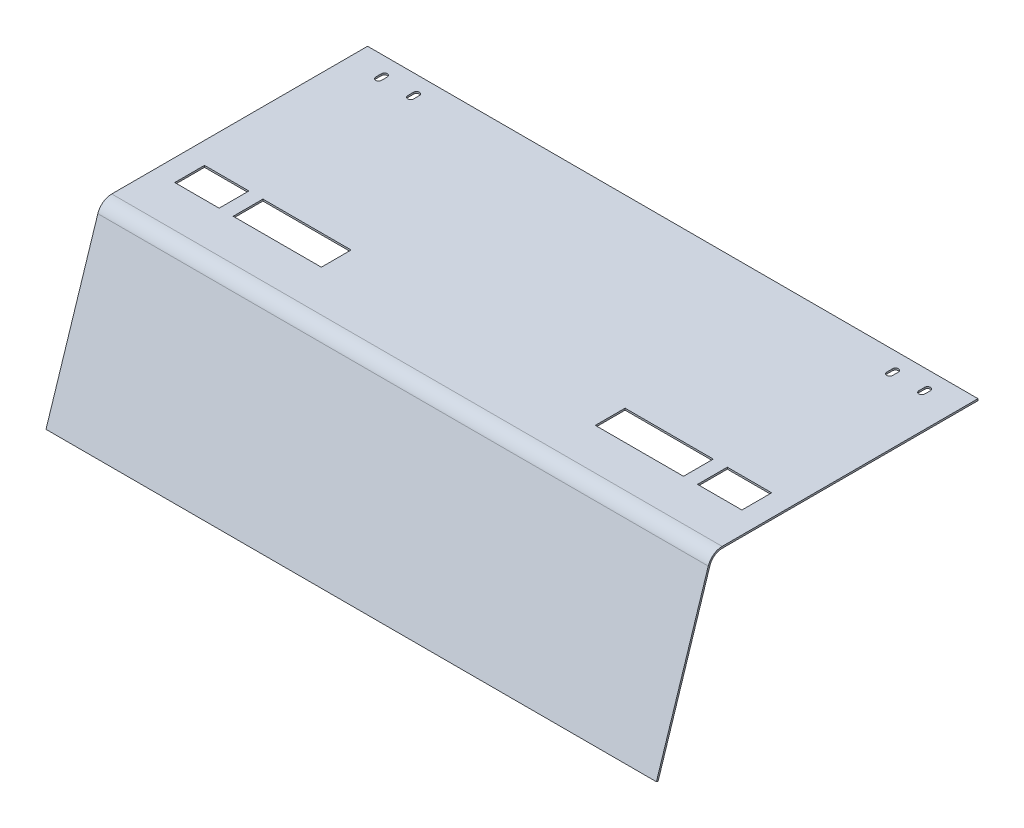
SolidWorks part; units mm, degrees
material "6061 합금"
ref_plane "정면" through (0, 0, 0) normal (0, 0, 1) x (1, 0, 0)
ref_plane "윗면" through (0, 0, 0) normal (0, 1, 0) x (1, 0, 0)
ref_plane "우측면" through (0, 0, 0) normal (1, 0, 0) x (0, 0, -1)
sketch "스케치1" plane through (0, 0, 0) normal (0, 1, 0) x (1, 0, 0)
  line L0 (-209, 87.105) -> (-209, -88.105)
  line L1 (-210, 88.105) -> (210, 88.105) construction
  line L2 (-210, 88.105) -> (-210, -88.105) construction
  line L3 (-210, -88.105) -> (210, -88.105) construction
  line L4 (210, 88.105) -> (210, -88.105) construction
  line L5 (-210, 88.105) -> (210, -88.105) construction
  line L6 (-210, -88.105) -> (210, 88.105) construction
  line L7 (-209, 87.105) -> (209, 87.105)
  line L8 (209, 87.105) -> (209, -88.105)
  line L9 (-209, -88.105) -> (209, -88.105)
  point P0 (0, 0)
  dimension "D1" = 176.21
  dimension "D2" = 420
  dimension "D3" = 1
extrude "보스-돌출1" add sketch "스케치1" along normal blind 1.2
sketch "스케치2" plane through (0, 0, 0) normal (1, 0, 0) x (0, 0, -1)
  line L0 (-97.6231, -5.7331) -> (-133.1196, -115.8954)
  line L7 (-96.4809, -6.1011) -> (-131.9775, -116.2635)
  line L8 (-133.1196, -115.8954) -> (-131.9775, -116.2635)
  line L10 (-88.105, 0) -> (87.105, 0)
  line L11 (87.105, 0) -> (87.105, 1.2)
  line L12 (87.105, 1.2) -> (-88.105, 1.2)
  line L13 (-88.105, 1.2) -> (-88.105, 0)
  line L17 (-88.105, 1.2) -> (-88.105, 0)
  arc A0 (-88.105, 1.2) -> (-97.6231, -5.7331) centre (-88.105, -8.8) ccw
  arc A1 (-88.105, 0) -> (-96.4809, -6.1011) centre (-88.105, -8.8) ccw
  dimension "D1" = 0
  dimension "D4" = 115.74
  dimension "D5" = 1.2
extrude "보스-돌출2" add sketch "스케치2" along normal up to vertex (209 mm away) and the other way up to vertex (209 mm away) up to point (209, 1.2, 88.105) other way up to point (-209, 1.2, 88.105)
sketch "스케치3" plane through (0, 1.2, 0) normal (0, 1, 0) x (1, 0, 0)
  line L0 (0, -87.105) -> (0, 87.105) construction
  line L1 (209, 87.105) -> (-209, 87.105) construction
  line L2 (-209, 87.105) -> (-209, -88.105) construction
  line L3 (-190, 87.105) -> (-160, 87.105)
  line L4 (-190, 87.105) -> (-190, 68.605)
  line L5 (-190, 68.605) -> (-160, 68.605)
  line L6 (-160, 87.105) -> (-160, 68.605)
  line L7 (-190, 73.605) -> (-160, 73.605) construction
  line L8 (-175, 87.105) -> (-175, 68.605) construction
  line L9 (-162, 75.605) -> (-162, 71.605)
  line L10 (-166, 75.605) -> (-166, 71.605)
  line L11 (-184, 75.605) -> (-184, 71.605)
  line L12 (-188, 75.605) -> (-188, 71.605)
  line L13 (175, 87.105) -> (175, 68.605) construction
  line L14 (190, 73.605) -> (160, 73.605) construction
  line L15 (188, 75.605) -> (188, 71.605)
  line L16 (184, 75.605) -> (184, 71.605)
  line L17 (166, 75.605) -> (166, 71.605)
  line L18 (162, 75.605) -> (162, 71.605)
  line L19 (160, 87.105) -> (160, 68.605)
  line L20 (190, 68.605) -> (160, 68.605)
  line L21 (190, 87.105) -> (190, 68.605)
  line L22 (190, 87.105) -> (160, 87.105)
  circle A0 centre (-164, 73.605) radius 2
  circle A1 centre (-164, 71.605) radius 2
  circle A2 centre (-164, 75.605) radius 2
  circle A3 centre (-186, 75.605) radius 2
  circle A4 centre (-186, 71.605) radius 2
  circle A5 centre (-186, 73.605) radius 2
  circle A6 centre (186, 73.605) radius 2
  circle A7 centre (186, 71.605) radius 2
  circle A8 centre (186, 75.605) radius 2
  circle A9 centre (164, 75.605) radius 2
  circle A10 centre (164, 71.605) radius 2
  circle A11 centre (164, 73.605) radius 2
  point P6 (0, 0)
  dimension "D6" = 4
  dimension "D1" = 19
  dimension "D2" = 30
  dimension "D3" = 18.5
  dimension "D4" = 5
  dimension "D5" = 22
extrude "컷-돌출1" cut sketch "스케치3" against normal up to next (1.2 mm away) contours A4 A5 | A5 A4 | A5 A4 A3 | A5 A3 A4 | A5 A3 | A3 A5 | L12 A5 A3 | A4 A5 L12 | L11 A5 A4 | A3 A5 L11 | A0 A2 | A2 A0 | A0 A1 | A1 A0 | A1 A0 L10 | A2 A0 A1 | A2 L10 A0 | A1 L9 A0 | A2 A1 A0 | A2 A0 L9 | A11 A10 | A11 A9 | A9 A11 | L18 A11 A9 | A11 A10 A9 | A10 A11 L18 | A11 A9 A10 | A9 A11 L17 | L17 A11 A10 | A10 A11 | A7 A6 | A6 A7 | A8 A6 | A6 A8 | A8 L16 A6 | A8 A6 A7 | A7 A6 L16 | A8 A6 L15 | A8 A7 A6 | A7 L15 A6
ref_plane "평면1" through (0, 17.4173, 3.332) normal (0, 0.9822, 0.1879) x (1, 0, 0)
sketch "스케치4" plane through (0, 17.4173, 3.332) normal (0, 0.9822, 0.1879) x (1, 0, 0)
  line L1 (-209, -86.3103) -> (209, -86.3103) construction
  line L2 (-209, -63.4603) -> (209, -63.4603) construction
  line L3 (-209, 85.779) -> (-209, -86.3103) construction
  line L4 (209, -86.3103) -> (209, 85.779) construction
  line L5 (0, -85.779) -> (0, 85.779) construction
  line L6 (209, 85.779) -> (-209, 85.779) construction
  line L7 (194, -33.4603) -> (164, -33.4603) construction
  line L8 (-194, -63.4603) -> (-164, -63.4603) construction
  line L9 (-194, -63.4603) -> (-194, -33.4603) construction
  line L10 (-194, -33.4603) -> (-164, -33.4603) construction
  line L11 (-164, -63.4603) -> (-164, -33.4603) construction
  line L12 (164, -63.4603) -> (164, -33.4603) construction
  line L13 (194, -63.4603) -> (164, -63.4603) construction
  line L14 (194, -63.4603) -> (194, -33.4603) construction
  line L15 (154, -33.4603) -> (94, -33.4603) construction
  line L16 (-154, -63.4603) -> (-94, -63.4603) construction
  line L17 (-154, -63.4603) -> (-154, -33.4603) construction
  line L18 (-154, -33.4603) -> (-94, -33.4603) construction
  line L19 (-94, -63.4603) -> (-94, -33.4603) construction
  line L20 (94, -63.4603) -> (94, -33.4603) construction
  line L21 (154, -63.4603) -> (94, -63.4603) construction
  line L22 (154, -63.4603) -> (154, -33.4603) construction
  line L23 (-209, -86.3103) -> (209, -86.3103) construction
  circle A0 centre (-179, -48.4603) radius 3
  circle A1 centre (-124, -48.4603) radius 3
  circle A2 centre (124, -48.4603) radius 3
  circle A3 centre (179, -48.4603) radius 3
  point P14 (0, 0)
  dimension "D1" = 22.85
  dimension "D2" = 30
  dimension "D3" = 30
  dimension "D4" = 15
  dimension "D5" = 60
  dimension "D6" = 30
  dimension "D7" = 10
extrude "컷-돌출2" cut sketch "스케치4" against normal up to next
sketch "스케치7" plane through (0, 1.2, 0) normal (0, 1, 0) x (1, 0, 0)
  line L0 (0, 0) -> (0, -68.6419) construction
  line L1 (-194.2, -39.3686) -> (-163.8, -39.3686)
  line L2 (-194.2, -39.3686) -> (-194.2, -59.7686)
  line L3 (-194.2, -59.7686) -> (-163.8, -59.7686)
  line L4 (-163.8, -39.3686) -> (-163.8, -59.7686)
  line L5 (-194.2, -39.3686) -> (-163.8, -59.7686) construction
  line L6 (-194.2, -59.7686) -> (-163.8, -39.3686) construction
  line L7 (-154.2, -39.3686) -> (-93.8, -39.3686)
  line L8 (-154.2, -39.3686) -> (-154.2, -59.7686)
  line L9 (-154.2, -59.7686) -> (-93.8, -59.7686)
  line L10 (-93.8, -39.3686) -> (-93.8, -59.7686)
  line L11 (-154.2, -39.3686) -> (-93.8, -59.7686) construction
  line L12 (-154.2, -59.7686) -> (-93.8, -39.3686) construction
  line L13 (194.2, -59.7686) -> (163.8, -59.7686)
  line L14 (163.8, -39.3686) -> (163.8, -59.7686)
  line L15 (194.2, -39.3686) -> (163.8, -39.3686)
  line L16 (194.2, -39.3686) -> (194.2, -59.7686)
  line L17 (154.2, -59.7686) -> (93.8, -59.7686)
  line L18 (93.8, -39.3686) -> (93.8, -59.7686)
  line L19 (154.2, -39.3686) -> (93.8, -39.3686)
  line L20 (154.2, -39.3686) -> (154.2, -59.7686)
  ellipse E0 centre (-179, -49.5686) end of major axis (-179, -52.623) minor radius 3 construction
  ellipse E1 centre (-179, -49.5686) end of major axis (-179, -52.623) minor radius 3 construction
  ellipse E2 centre (-124, -49.5686) end of major axis (-124, -52.623) minor radius 3 construction
  ellipse E3 centre (-124, -49.5686) end of major axis (-124, -52.623) minor radius 3 construction
  point P0 (-179, -49.5686)
  dimension "D1" = 30.4
  dimension "D2" = 20.4
  dimension "D3" = 60.4
  dimension "D4" = 20.4
extrude "컷-돌출3" cut sketch "스케치7" against normal up to next
